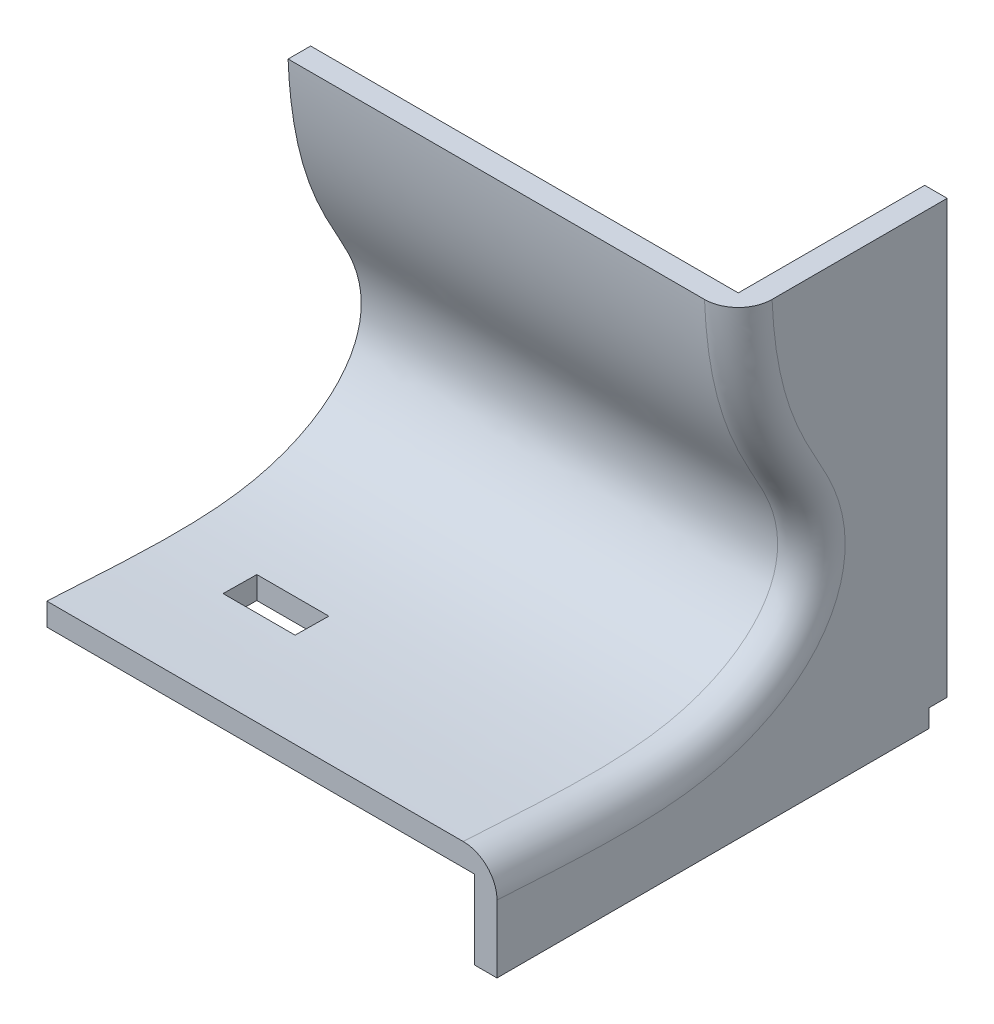
SolidWorks part; units mm, degrees
ref_plane "정면" through (0, 0, 0) normal (0, 0, 1) x (1, 0, 0)
ref_plane "윗면" through (0, 0, 0) normal (0, 1, 0) x (1, 0, 0)
ref_plane "우측면" through (0, 0, 0) normal (1, 0, 0) x (0, 0, -1)
sketch "스케치1" plane through (0, 0, 0) normal (0, 0, 1) x (1, 0, 0)
  line L1 (-40, 50) -> (40, 50)
  line L2 (-40, 50) -> (-40, -50)
  line L3 (-40, -50) -> (40, -50)
  line L4 (40, 50) -> (40, -50)
  line L5 (-40, 50) -> (40, -50) construction
  line L6 (-40, -50) -> (40, 50) construction
  point P0 (0, 0)
  dimension "D1" = 80
  dimension "D2" = 100
extrude "보스-돌출1" add sketch "스케치1" against normal blind 100
sketch "스케치2" plane through (40, 0, 0) normal (1, 0, 0) x (0, 0, -1)
  line L0 (100, -50) -> (100, 50) construction
  line L1 (0, 50) -> (80, 50)
  line L2 (0, 50) -> (0, -35)
  line L3 (0, -35) -> (80, -35)
  line L4 (80, 50) -> (80, -35)
  line L5 (100, -50) -> (0, -50) construction
  dimension "D1" = 20
  dimension "D2" = 15
extrude "컷-돌출1" cut sketch "스케치2" against normal blind 90
sketch "스케치5" plane through (40, 0, 0) normal (1, 0, 0) x (0, 0, -1)
  line L0 (0, -50) -> (0, -35) construction
  line L1 (100, 50) -> (80, 50) construction
  line L2 (96, 50) -> (80, 50)
  line L4 (80, 50) -> (80, -35)
  line L6 (80, -35) -> (0, -35)
  line L8 (80, 50) -> (80, -35)
  line L9 (80, -35) -> (0, -35)
  line L10 (0, -35) -> (0, -50)
  line L11 (0, -50) -> (100, -50)
  line L12 (100, -50) -> (100, 50)
  line L13 (100, 50) -> (80, 50)
  line L15 (80, -35) -> (0, -35)
  line L16 (0, -35) -> (0, -50)
  line L17 (0, -50) -> (100, -50)
  line L18 (100, -50) -> (100, 50)
  line L19 (100, 50) -> (80, 50)
  line L20 (80, 50) -> (80, -35)
  spline S0 degree 3 poles (0, -39.3767) (18.6089, -37.8138) (60.522, -41.4488) (82.6293, -41.815) (94.477, -29.9816) (72.3521, -11.4072) (96, 50) knots 0 0 0 0 0.361872 0.526262 0.755385 1 1 1 1
  dimension "D9" = 9.5231
  dimension "D2" = 22.8534
  dimension "D3" = 11
  dimension "D4" = 8.7853
  dimension "D5" = 36.2853
  dimension "D6" = 13.0435
  dimension "D7" = 22.021
  dimension "D8" = 20
  dimension "D10" = 16
  dimension "D11" = 4.3767
  dimension "D1" = 0
extrude "컷-돌출5" cut sketch "스케치5" against normal through all
shell "쉘2" thickness 2
fillet "필렛1" radius 3 1 edges at (0, 50, -96)
fillet "필렛2" radius 5 1 edges at (0, -39.3767, 0)
fillet "필렛3" radius 3 10 edges at (-40, -47.0329, 0) (-40, -40.6133, -1.3834) (-40, 50, -99.0322) (-40, 49.4694, -96.3609) (40, -47.0329, 0) (40, -40.6133, -1.3834) (40, 50, -99.0322) (40, 49.4694, -96.3609)
ref_plane "평면1" through (40, 47, -98.0645) normal (0, -0.9348, 0.3551) x (-1, 0, 0)
sketch "스케치6" plane through (0, 0, -100) normal (0, 0, -1) x (-1, 0, 0)
  line L0 (-40, -50) -> (-40, 47) construction
  line L1 (-40, -50) -> (-40, 47)
  line L2 (-40, 10) -> (40, 10)
  line L3 (40, 47) -> (40, -50) construction
  line L4 (0, 20.2731) -> (0, 42) construction
  line L5 (-11.9, 11.25) -> (-8.1, 11.25)
  line L6 (-11.9, 11.25) -> (-11.9, 8.75)
  line L7 (-11.9, 8.75) -> (-8.1, 8.75)
  line L8 (-8.1, 11.25) -> (-8.1, 8.75)
  line L9 (-11.9, 11.25) -> (-8.1, 8.75) construction
  line L10 (-11.9, 8.75) -> (-8.1, 11.25) construction
  line L11 (-37, 50) -> (37, 50) construction
  line L12 (11.9, 8.75) -> (8.1, 11.25) construction
  line L13 (11.9, 11.25) -> (8.1, 8.75) construction
  line L14 (8.1, 11.25) -> (8.1, 8.75)
  line L15 (11.9, 8.75) -> (8.1, 8.75)
  line L16 (11.9, 11.25) -> (11.9, 8.75)
  line L17 (11.9, 11.25) -> (8.1, 11.25)
  point P7 (-10, 10)
  point P19 (10, 10)
  dimension "D1" = 3.8
  dimension "D2" = 2.5
  dimension "D3" = 10
  dimension "D4" = 40
extrude "컷-돌출6" cut sketch "스케치6" against normal blind 85 contours L8 L5 L6 L2 | L8 L2 L6 L7 | L16 L2 L14 L15
sketch "스케치8" plane through (0, 50, 0) normal (0, 1, 0) x (1, 0, 0)
  line L0 (-37, 81.3983) -> (-40, 71.8589)
  line L1 (-40, 96) -> (-40, 0) construction
  line L2 (-40, 71.8589) -> (40, 71.8589)
  line L3 (40, 0) -> (40, 96) construction
  line L4 (0, 76.7018) -> (0, 80.7018) construction
  line L5 (-13.2, 71.8589) -> (-6.8, 71.8589)
  line L6 (-13.2, 71.8589) -> (-13.2, 68.8589)
  line L7 (-13.2, 68.8589) -> (-6.8, 68.8589)
  line L8 (-6.8, 71.8589) -> (-6.8, 68.8589)
  line L9 (-13.2, 71.8589) -> (-6.8, 68.8589) construction
  line L10 (-13.2, 68.8589) -> (-6.8, 71.8589) construction
  line L12 (13.2, 68.8589) -> (6.8, 71.8589) construction
  line L13 (13.2, 71.8589) -> (6.8, 68.8589) construction
  line L14 (6.8, 71.8589) -> (6.8, 68.8589)
  line L15 (13.2, 68.8589) -> (6.8, 68.8589)
  line L16 (13.2, 71.8589) -> (13.2, 68.8589)
  line L17 (13.2, 71.8589) -> (6.8, 71.8589)
  point P5 (-10, 70.3589)
  point P14 (0, 71.8589)
  point P20 (10, 70.3589)
  dimension "D1" = 10
  dimension "D2" = 6.4
  dimension "D3" = 3
  dimension "D4" = 10
extrude "컷-돌출7" cut sketch "스케치8" against normal blind 100 contours L8 L2 L6 L7 | L8 L5 L6 L2 | L16 L17 L14 L2 | L16 L2 L14 L15
sketch "스케치11" plane through (0, 0, -100) normal (0, 0, -1) x (-1, 0, 0)
  line L1 (-22.3234, 3.6269) -> (45.6766, 3.6269) construction
  line L2 (0, 45.5744) -> (0, 67.3013) construction
  line L9 (-37, 50) -> (37, 50) construction
  line L10 (-11, 4.1269) -> (-9, 4.1269)
  line L15 (-11, 4.1269) -> (-11, 3.1269)
  line L16 (-11, 3.1269) -> (-9, 3.1269)
  line L17 (-9, 4.1269) -> (-9, 3.1269)
  line L18 (-11, 4.1269) -> (-9, 3.1269) construction
  line L19 (-11, 3.1269) -> (-9, 4.1269) construction
  line L20 (11, 3.1269) -> (9, 3.1269)
  line L21 (11, 4.1269) -> (11, 3.1269)
  line L22 (11, 4.1269) -> (9, 4.1269)
  line L23 (9, 4.1269) -> (9, 3.1269)
  point P2 (-10, 3.6269)
  dimension "D2" = 2
  dimension "D3" = 1
  dimension "D1" = 46.3731
  dimension "D4" = 10
extrude "컷-돌출8" cut sketch "스케치11" against normal through all
scale "축척1" bodies to scale 119 scale about origin uniform scaling yes scale factor 5
sketch "스케치12" plane through (0, 0, 0) normal (0, 0, 1) x (1, 0, 0)
  line L0 (200, -222.4272) -> (200, 235) construction
  line L1 (-200, 250) -> (200, 250)
  line L2 (-200, 250) -> (-200, -50)
  line L3 (-200, -50) -> (200, -50)
  line L4 (200, 250) -> (200, -50)
  line L5 (-185, 250) -> (185, 250) construction
  line L6 (-200, 235) -> (-200, -222.4272) construction
  line L7 (0, -50) -> (0, -250)
  line L8 (-185, -250) -> (185, -250) construction
  line L9 (0, -250) -> (200, -250)
  line L11 (200, -250) -> (200, -50)
  line L12 (-200, -50) -> (-200, -250)
  line L13 (-200, -250) -> (0, -250)
  line M7 (185, -220.3291) -> (-185, -220.3291)
  line M8 (-185, -220.3291) -> (-185, -250)
  line M9 (-185, -250) -> (185, -250)
  dimension "D1" = 200
extrude "컷-돌출11" cut sketch "스케치12" against normal through all contours L4 L1 L2 L3 | L12 L13 L7 L3 M8 M7 | L7 M7 M8 M9
sketch "스케치14" plane through (0, -250, 0) normal (0, -1, 0) x (1, 0, 0)
  line L0 (200, -500) -> (200, -15) construction
  line L1 (0, 0) -> (200, 0)
  line L2 (0, 0) -> (0, -300)
  line L3 (0, -300) -> (200, -300)
  line L4 (200, 0) -> (200, -300)
  line L5 (190, -500) -> (200, -500) construction
  dimension "D1" = 200
extrude "컷-돌출12" cut sketch "스케치14" against normal through all
sketch "스케치15" plane through (200, 0, 0) normal (1, 0, 0) x (0, 0, -1)
  line L0 (500, -250) -> (500, -50) construction
  line L1 (500, -242) -> (492, -242)
  line L2 (500, -242) -> (500, -250)
  line L3 (500, -250) -> (492, -250)
  line L4 (492, -242) -> (492, -250)
  line L5 (500, -250) -> (300, -250) construction
  dimension "D1" = 8
  dimension "D2" = 8
extrude "컷-돌출13" cut sketch "스케치15" against normal blind 10
